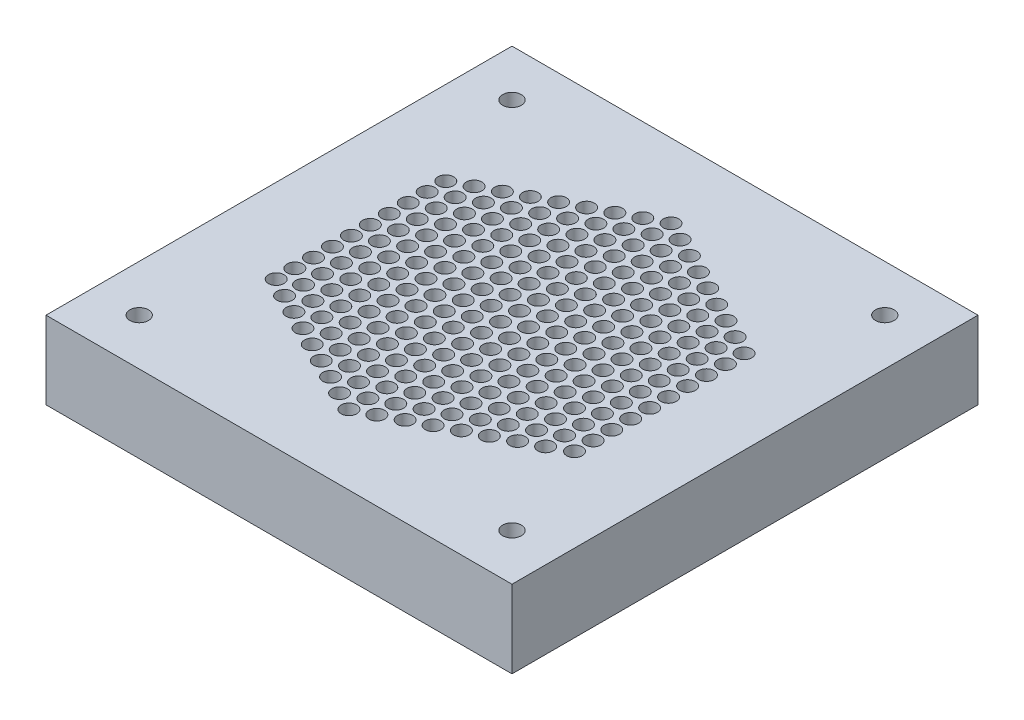
SolidWorks part; units mm, degrees
ref_plane "Front Plane" through (0, 0, 0) normal (0, 0, 1) x (1, 0, 0)
ref_plane "Top Plane" through (0, 0, 0) normal (0, 1, 0) x (1, 0, 0)
ref_plane "Right Plane" through (0, 0, 0) normal (1, 0, 0) x (0, 0, -1)
ref_plane "Plane1"
sketch "Sketch1" plane through (0, 0, 0) normal (0, 1, 0) x (-1, 0, 0)
  line L0 (-75, 75) -> (75, 75)
  line L1 (75, 75) -> (75, -75)
  line L2 (75, -75) -> (-75, -75)
  line L3 (-75, -75) -> (-75, 75)
  circle A0 centre (0, 52.5) radius 2.5
  circle A1 centre (0, 46.4) radius 2.5
  circle A2 centre (0, 40.3) radius 2.5
  circle A3 centre (0, 34.2) radius 2.5
  circle A4 centre (0, 28.1) radius 2.5
  circle A5 centre (0, 22) radius 2.5
  circle A6 centre (0, 15.9) radius 2.5
  circle A7 centre (0, 9.8) radius 2.5
  circle A8 centre (0, 3.7) radius 2.5
  circle A9 centre (0, -2.4) radius 2.5
  circle A10 centre (0, -8.5) radius 2.5
  circle A11 centre (0, -14.6) radius 2.5
  circle A12 centre (0, -20.7) radius 2.5
  circle A13 centre (0, -26.8) radius 2.5
  circle A14 centre (0, -32.9) radius 2.5
  circle A15 centre (0, -39) radius 2.5
  circle A16 centre (0, -45.1) radius 2.5
  circle A17 centre (0, -51.2) radius 2.5
  circle A18 centre (6, -35.9) radius 2.5
  circle A19 centre (6, -29.8) radius 2.5
  circle A20 centre (6, -42) radius 2.5
  circle A21 centre (6, -48.1) radius 2.5
  circle A22 centre (6, -23.7) radius 2.5
  circle A23 centre (6, -17.6) radius 2.5
  circle A24 centre (6, -11.5) radius 2.5
  circle A25 centre (6, -5.4) radius 2.5
  circle A26 centre (6, 0.7) radius 2.5
  circle A27 centre (6, 19) radius 2.5
  circle A28 centre (6, 12.9) radius 2.5
  circle A29 centre (6, 6.8) radius 2.5
  circle A30 centre (6, 37.3) radius 2.5
  circle A31 centre (6, 31.2) radius 2.5
  circle A32 centre (6, 25.1) radius 2.5
  circle A33 centre (6, 43.4) radius 2.5
  circle A34 centre (6, 49.5) radius 2.5
  circle A35 centre (18, -23.7) radius 2.5
  circle A36 centre (18, -35.9) radius 2.5
  circle A37 centre (18, -29.8) radius 2.5
  circle A38 centre (18, -42) radius 2.5
  circle A39 centre (18, -11.5) radius 2.5
  circle A40 centre (18, -17.6) radius 2.5
  circle A41 centre (18, -5.4) radius 2.5
  circle A42 centre (18, 0.7) radius 2.5
  circle A43 centre (18, 6.8) radius 2.5
  circle A44 centre (18, 12.9) radius 2.5
  circle A45 centre (18, 25.1) radius 2.5
  circle A46 centre (18, 31.2) radius 2.5
  circle A47 centre (18, 37.3) radius 2.5
  circle A48 centre (18, 43.4) radius 2.5
  circle A49 centre (18, 19) radius 2.5
  circle A50 centre (30, -23.7) radius 2.5
  circle A51 centre (30, -35.9) radius 2.5
  circle A52 centre (30, -29.8) radius 2.5
  circle A53 centre (30, -11.5) radius 2.5
  circle A54 centre (30, -17.6) radius 2.5
  circle A55 centre (30, -5.4) radius 2.5
  circle A56 centre (30, 0.7) radius 2.5
  circle A57 centre (30, 6.8) radius 2.5
  circle A58 centre (30, 12.9) radius 2.5
  circle A59 centre (30, 25.1) radius 2.5
  circle A60 centre (30, 31.2) radius 2.5
  circle A61 centre (30, 37.3) radius 2.5
  circle A62 centre (30, 19) radius 2.5
  circle A63 centre (42, -23.7) radius 2.5
  circle A64 centre (42, -29.8) radius 2.5
  circle A65 centre (42, -11.5) radius 2.5
  circle A66 centre (42, -17.6) radius 2.5
  circle A67 centre (42, -5.4) radius 2.5
  circle A68 centre (42, 0.7) radius 2.5
  circle A69 centre (42, 6.8) radius 2.5
  circle A70 centre (42, 12.9) radius 2.5
  circle A71 centre (42, 25.1) radius 2.5
  circle A72 centre (42, 31.2) radius 2.5
  circle A73 centre (42, 19) radius 2.5
  circle A74 centre (-6, -23.7) radius 2.5
  circle A75 centre (-6, -35.9) radius 2.5
  circle A76 centre (-6, -29.8) radius 2.5
  circle A77 centre (-6, -42) radius 2.5
  circle A78 centre (-6, -48.1) radius 2.5
  circle A79 centre (-6, -11.5) radius 2.5
  circle A80 centre (-6, -17.6) radius 2.5
  circle A81 centre (-6, -5.4) radius 2.5
  circle A82 centre (-6, 0.7) radius 2.5
  circle A83 centre (-6, 6.8) radius 2.5
  circle A84 centre (-6, 12.9) radius 2.5
  circle A85 centre (-6, 25.1) radius 2.5
  circle A86 centre (-6, 31.2) radius 2.5
  circle A87 centre (-6, 37.3) radius 2.5
  circle A88 centre (-6, 43.4) radius 2.5
  circle A89 centre (-6, 19) radius 2.5
  circle A90 centre (-6, 49.5) radius 2.5
  circle A91 centre (-18, -23.7) radius 2.5
  circle A92 centre (-18, -35.9) radius 2.5
  circle A93 centre (-18, -29.8) radius 2.5
  circle A94 centre (-18, -42) radius 2.5
  circle A95 centre (-18, -11.5) radius 2.5
  circle A96 centre (-18, -17.6) radius 2.5
  circle A97 centre (-18, -5.4) radius 2.5
  circle A98 centre (-18, 0.7) radius 2.5
  circle A99 centre (-18, 6.8) radius 2.5
  circle A100 centre (-18, 12.9) radius 2.5
  circle A101 centre (-18, 25.1) radius 2.5
  circle A102 centre (-18, 31.2) radius 2.5
  circle A103 centre (-18, 37.3) radius 2.5
  circle A104 centre (-18, 43.4) radius 2.5
  circle A105 centre (-18, 19) radius 2.5
  circle A106 centre (-30, -23.7) radius 2.5
  circle A107 centre (-30, -35.9) radius 2.5
  circle A108 centre (-30, -29.8) radius 2.5
  circle A109 centre (-30, -11.5) radius 2.5
  circle A110 centre (-30, -17.6) radius 2.5
  circle A111 centre (-30, -5.4) radius 2.5
  circle A112 centre (-30, 0.7) radius 2.5
  circle A113 centre (-30, 6.8) radius 2.5
  circle A114 centre (-30, 12.9) radius 2.5
  circle A115 centre (-30, 25.1) radius 2.5
  circle A116 centre (-30, 31.2) radius 2.5
  circle A117 centre (-30, 37.3) radius 2.5
  circle A118 centre (-30, 19) radius 2.5
  circle A119 centre (-42, -23.7) radius 2.5
  circle A120 centre (-42, -29.8) radius 2.5
  circle A121 centre (-42, -11.5) radius 2.5
  circle A122 centre (-42, -17.6) radius 2.5
  circle A123 centre (-42, -5.4) radius 2.5
  circle A124 centre (-42, 0.7) radius 2.5
  circle A125 centre (-42, 6.8) radius 2.5
  circle A126 centre (-42, 12.9) radius 2.5
  circle A127 centre (-42, 25.1) radius 2.5
  circle A128 centre (-42, 31.2) radius 2.5
  circle A129 centre (-42, 19) radius 2.5
  circle A130 centre (-12, -32.9) radius 2.5
  circle A131 centre (-12, -39) radius 2.5
  circle A132 centre (-12, -45.1) radius 2.5
  circle A133 centre (-12, -2.4) radius 2.5
  circle A134 centre (-12, -8.5) radius 2.5
  circle A135 centre (-12, -14.6) radius 2.5
  circle A136 centre (-12, -26.8) radius 2.5
  circle A137 centre (-12, -20.7) radius 2.5
  circle A138 centre (-12, 3.7) radius 2.5
  circle A139 centre (-12, 28.1) radius 2.5
  circle A140 centre (-12, 22) radius 2.5
  circle A141 centre (-12, 15.9) radius 2.5
  circle A142 centre (-12, 9.8) radius 2.5
  circle A143 centre (-12, 40.3) radius 2.5
  circle A144 centre (-12, 34.2) radius 2.5
  circle A145 centre (-12, 46.4) radius 2.5
  circle A146 centre (-24, -32.9) radius 2.5
  circle A147 centre (-24, -39) radius 2.5
  circle A148 centre (-24, -2.4) radius 2.5
  circle A149 centre (-24, -8.5) radius 2.5
  circle A150 centre (-24, -14.6) radius 2.5
  circle A151 centre (-24, -26.8) radius 2.5
  circle A152 centre (-24, -20.7) radius 2.5
  circle A153 centre (-24, 3.7) radius 2.5
  circle A154 centre (-24, 28.1) radius 2.5
  circle A155 centre (-24, 22) radius 2.5
  circle A156 centre (-24, 15.9) radius 2.5
  circle A157 centre (-24, 9.8) radius 2.5
  circle A158 centre (-24, 40.3) radius 2.5
  circle A159 centre (-24, 34.2) radius 2.5
  circle A160 centre (-36, -32.9) radius 2.5
  circle A161 centre (-36, -2.4) radius 2.5
  circle A162 centre (-36, -8.5) radius 2.5
  circle A163 centre (-36, -14.6) radius 2.5
  circle A164 centre (-36, -26.8) radius 2.5
  circle A165 centre (-36, -20.7) radius 2.5
  circle A166 centre (-36, 3.7) radius 2.5
  circle A167 centre (-36, 28.1) radius 2.5
  circle A168 centre (-36, 22) radius 2.5
  circle A169 centre (-36, 15.9) radius 2.5
  circle A170 centre (-36, 9.8) radius 2.5
  circle A171 centre (-36, 34.2) radius 2.5
  circle A172 centre (24, -32.9) radius 2.5
  circle A173 centre (24, -39) radius 2.5
  circle A174 centre (24, -2.4) radius 2.5
  circle A175 centre (24, -8.5) radius 2.5
  circle A176 centre (24, -14.6) radius 2.5
  circle A177 centre (24, -26.8) radius 2.5
  circle A178 centre (24, -20.7) radius 2.5
  circle A179 centre (24, 3.7) radius 2.5
  circle A180 centre (24, 28.1) radius 2.5
  circle A181 centre (24, 22) radius 2.5
  circle A182 centre (24, 15.9) radius 2.5
  circle A183 centre (24, 9.8) radius 2.5
  circle A184 centre (24, 40.3) radius 2.5
  circle A185 centre (24, 34.2) radius 2.5
  circle A186 centre (36, -32.9) radius 2.5
  circle A187 centre (36, -2.4) radius 2.5
  circle A188 centre (36, -8.5) radius 2.5
  circle A189 centre (36, -14.6) radius 2.5
  circle A190 centre (36, -26.8) radius 2.5
  circle A191 centre (36, -20.7) radius 2.5
  circle A192 centre (36, 3.7) radius 2.5
  circle A193 centre (36, 28.1) radius 2.5
  circle A194 centre (36, 22) radius 2.5
  circle A195 centre (36, 15.9) radius 2.5
  circle A196 centre (36, 9.8) radius 2.5
  circle A197 centre (36, 34.2) radius 2.5
  circle A198 centre (48, -2.4) radius 2.5
  circle A199 centre (48, -8.5) radius 2.5
  circle A200 centre (48, -14.6) radius 2.5
  circle A201 centre (48, -20.7) radius 2.5
  circle A202 centre (48, 3.7) radius 2.5
  circle A203 centre (48, 15.9) radius 2.5
  circle A204 centre (48, 9.8) radius 2.5
  circle A205 centre (12, -32.9) radius 2.5
  circle A206 centre (12, -39) radius 2.5
  circle A207 centre (12, -45.1) radius 2.5
  circle A208 centre (12, -2.4) radius 2.5
  circle A209 centre (12, -8.5) radius 2.5
  circle A210 centre (12, -14.6) radius 2.5
  circle A211 centre (12, -26.8) radius 2.5
  circle A212 centre (12, -20.7) radius 2.5
  circle A213 centre (12, 3.7) radius 2.5
  circle A214 centre (12, 28.1) radius 2.5
  circle A215 centre (12, 22) radius 2.5
  circle A216 centre (12, 15.9) radius 2.5
  circle A217 centre (12, 9.8) radius 2.5
  circle A218 centre (12, 40.3) radius 2.5
  circle A219 centre (12, 34.2) radius 2.5
  circle A220 centre (12, 46.4) radius 2.5
  circle A221 centre (-48, -2.4) radius 2.5
  circle A222 centre (-48, -8.5) radius 2.5
  circle A223 centre (-48, -14.6) radius 2.5
  circle A224 centre (-48, -20.7) radius 2.5
  circle A225 centre (-48, 3.7) radius 2.5
  circle A226 centre (-48, 15.9) radius 2.5
  circle A227 centre (-48, 9.8) radius 2.5
  circle A228 centre (48, 21.9) radius 2.5
  circle A229 centre (48, 27.9) radius 2.5
  circle A230 centre (48, -26.7) radius 2.5
  circle A231 centre (-48, 21.9) radius 2.5
  circle A232 centre (-48, 27.9) radius 2.5
  circle A233 centre (-48, -26.7) radius 2.5
  dimension "D3" = 5
  dimension "D1" = 150
  dimension "D2" = 150
  dimension "D4" = 6.1
  dimension "D5" = 6.7082
  dimension "D6" = 6.7082
  dimension "D7" = 12
  dimension "D8" = 6
  dimension "D9" = 6
  dimension "D10" = 6
  dimension "D11" = 6
extrude "Extrusion2" add sketch "Sketch1" along normal blind 25 contours L3 L2 L1 L0 A233 A232 A231 A230 A229 A228 A227 A226 A225 A224 A223 A222 A221 A220 A219 A218 A217 A216 A215 A214 A213 A212 A211
ref_plane "Plane2"
sketch "Sketch2" plane through (0, 0, 0) normal (0, -1, 0) x (1, 0, 0)
  circle A0 centre (-60, 60) radius 3
  circle A1 centre (60, 60) radius 3
  circle A2 centre (60, -60) radius 3
  circle A3 centre (-60, -60) radius 3
  dimension "D3" = 6
  dimension "D4" = 6
  dimension "D5" = 6
  dimension "D6" = 6
  dimension "D1" = 120
  dimension "D2" = 120
extrude "Extrusion3" cut sketch "Sketch2" against normal up to surface (25 mm away) contours A0 | A1 | A2 | A3 up to face at (48, 25, -24.2)
